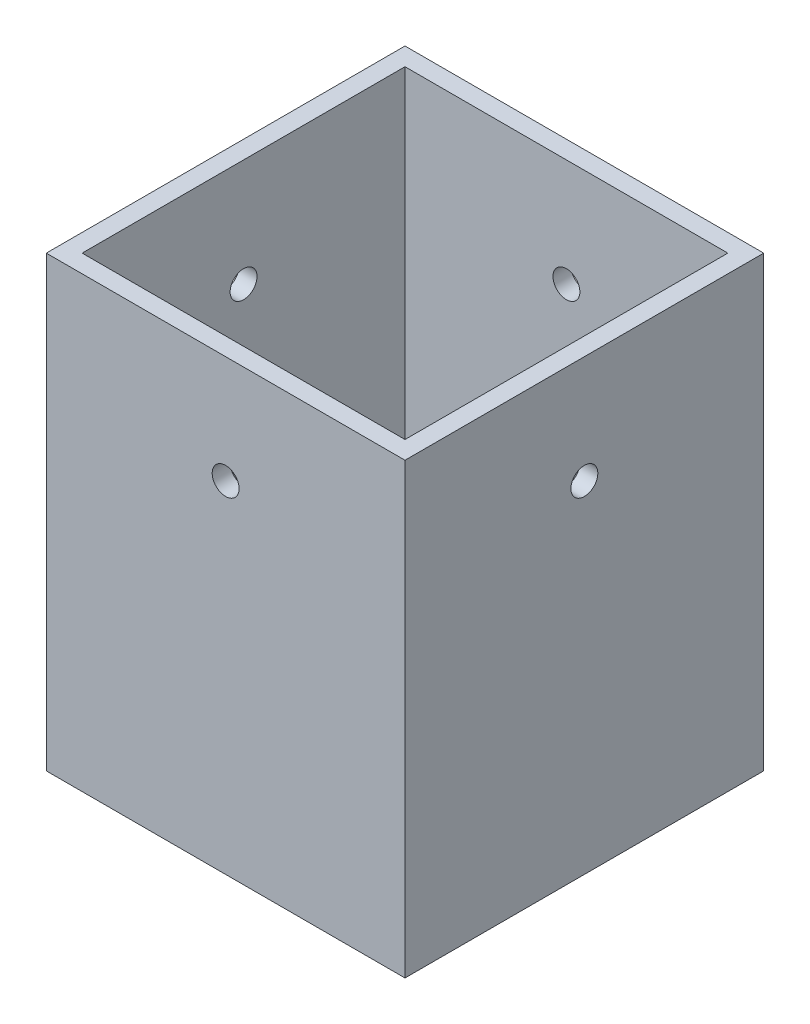
SolidWorks part; units mm, degrees
ref_plane "前视基准面" through (0, 0, 0) normal (0, 0, 1) x (1, 0, 0)
ref_plane "上视基准面" through (0, 0, 0) normal (0, 1, 0) x (1, 0, 0)
ref_plane "右视基准面" through (0, 0, 0) normal (1, 0, 0) x (0, 0, -1)
other "Configuration Table"
sketch "草图1" plane through (0, 0, 0) normal (0, 1, 0) x (1, 0, 0)
  line L1 (0, 0) -> (40, 0)
  line L2 (0, 0) -> (0, -40)
  line L3 (0, -40) -> (40, -40)
  line L4 (40, 0) -> (40, -40)
  dimension "D1" = 40
  dimension "D2" = 40
extrude "凸台-拉伸1" add sketch "草图1" along normal blind 50
sketch "草图2" plane through (0, 50, 0) normal (0, 1, 0) x (1, 0, 0)
  line L0 (20, 0) -> (20, -40) construction
  line L1 (40, 0) -> (0, 0) construction
  line L2 (0, -40) -> (40, -40) construction
  line L3 (0, -20) -> (40, -20) construction
  line L4 (0, 0) -> (0, -40) construction
  line L5 (40, -40) -> (40, 0) construction
  line L7 (38, -38) -> (2, -38)
  line L8 (38, -38) -> (38, -2)
  line L9 (38, -2) -> (2, -2)
  line L10 (2, -38) -> (2, -2)
  line L11 (38, -38) -> (2, -2) construction
  line L12 (38, -2) -> (2, -38) construction
  point P12 (20, -20)
  dimension "D1" = 36
  dimension "D2" = 36
extrude "切除-拉伸1" cut sketch "草图2" against normal blind 46
sketch "草图3" plane through (0, 0, 40) normal (0, 0, 1) x (1, 0, 0)
  line L0 (20, 50) -> (20, 0) construction
  line L1 (0, 50) -> (40, 50) construction
  line L2 (0, 0) -> (40, 0) construction
  circle A0 centre (20, 38) radius 1.5
  dimension "D1" = 3
  dimension "D2" = 12
extrude "切除-拉伸2" cut sketch "草图3" against normal blind 46
sketch "草图4" plane through (40, 0, 0) normal (1, 0, 0) x (0, 0, -1)
  line L0 (-20, 50) -> (-20, 0) construction
  line L1 (-40, 50) -> (0, 50) construction
  line L2 (-40, 0) -> (0, 0) construction
  circle A0 centre (-20, 38) radius 1.5
  dimension "D1" = 3
  dimension "D2" = 12
extrude "切除-拉伸3" cut sketch "草图4" against normal blind 46
